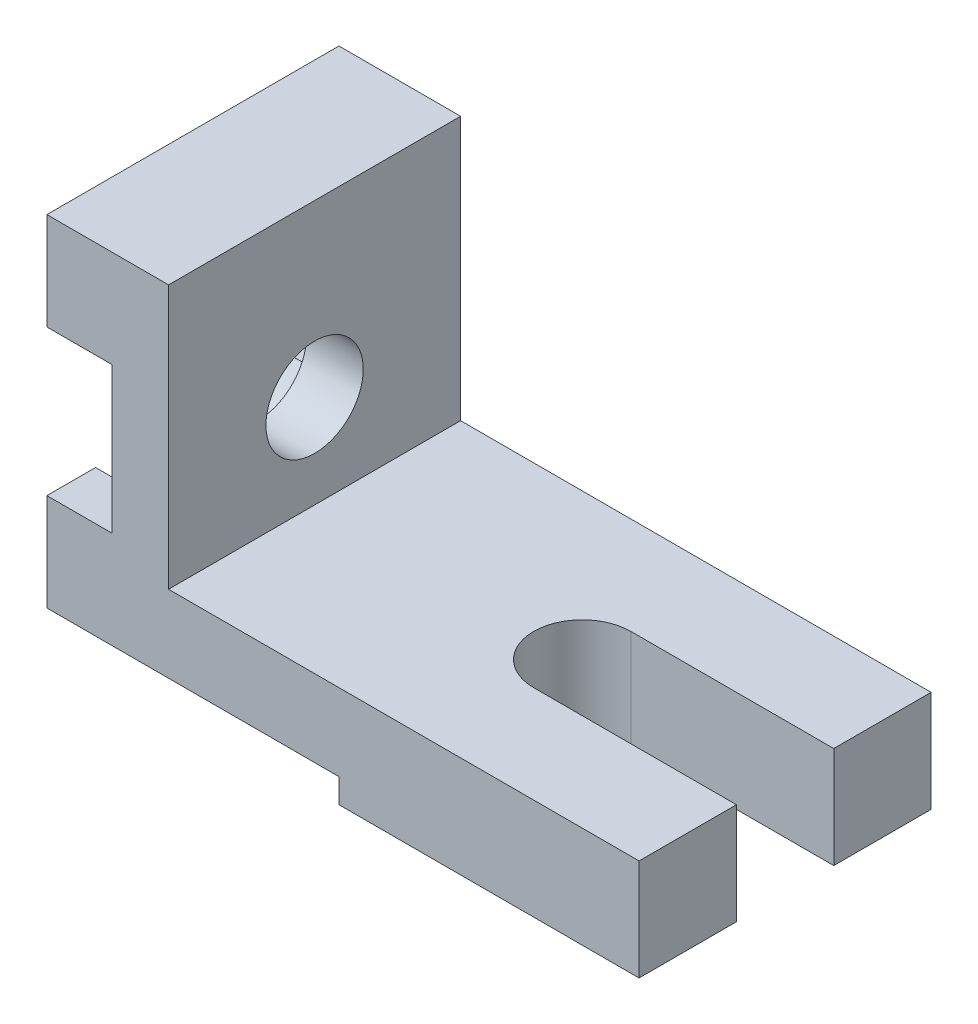
SolidWorks part; units mm, degrees
ref_plane "Front Plane" through (0, 0, 0) normal (0, 0, 1) x (1, 0, 0)
ref_plane "Top Plane" through (0, 0, 0) normal (0, 1, 0) x (1, 0, 0)
ref_plane "Right Plane" through (0, 0, 0) normal (1, 0, 0) x (0, 0, -1)
sketch "Sketch1" plane through (0, 0, 0) normal (0, 0, 1) x (1, 0, 0)
  line L0 (0, 0) -> (-146, 0)
  line L1 (-146, 0) -> (-146, 90)
  line L2 (-146, 90) -> (-116, 90)
  line L3 (-116, 90) -> (-116, 25)
  line L4 (-116, 25) -> (0, 25)
  line L5 (0, 25) -> (0, 0)
  dimension "D1" = 146
  dimension "D2" = 90
  dimension "D3" = 30
  dimension "D4" = 25
extrude "Boss-Extrude1" add sketch "Sketch1" along normal blind 72
sketch "Sketch2" plane through (0, 25, 0) normal (0, 1, 0) x (1, 0, 0)
  line L1 (-116, -72) -> (-116, 0) construction
  line L2 (0, -36) -> (-50, -36) construction
  line L3 (0, -48) -> (-50, -48)
  line L4 (0, -24) -> (-50, -24)
  line L5 (0, 0) -> (-116, 0) construction
  arc A1 (-50, -24) -> (-50, -48) centre (-50, -36) ccw
  point P4 (-25, -36)
  dimension "D2" = 12
  dimension "D1" = 50
  dimension "D3" = 66
  dimension "D4" = 36
extrude "Cut-Extrude2" cut sketch "Sketch2" against normal blind 25 and the other way through all
sketch "Sketch3" plane through (-146, 0, 0) normal (-1, 0, 0) x (0, 0, 1)
  line L4 (72, 0) -> (0, 0) construction
  line L6 (72, 0) -> (0, 0)
  line L8 (36, 0) -> (36, 48) construction
  line L9 (72, 6) -> (72, 0)
  line L10 (0, 65.664) -> (11.7517, 65.664)
  line L11 (60.2483, 65.664) -> (72, 65.664)
  line L12 (72, 6) -> (22, 6)
  line L13 (22, 6) -> (22, 0)
  line L14 (22, 0) -> (72, 0)
  circle A2 centre (36, 48) radius 30
  circle A3 centre (36, 48) radius 12
  dimension "D1" = 60
  dimension "D2" = 24
  dimension "D3" = 6
  dimension "D4" = 50
extrude "Cut-Extrude4" cut sketch "Sketch3" against normal blind 72 contours L9 L12 L13 L14
sketch "Sketch4" plane through (-146, 0, 0) normal (-1, 0, 0) x (0, 0, 1)
  line L1 (22, 0) -> (0, 0) construction
  line L2 (22, 0) -> (72, 0) construction
  line L3 (36, 0) -> (36, 18) construction
  line L4 (0, 90) -> (0, 0) construction
  line L5 (0, 66) -> (12, 66)
  line L6 (60, 66) -> (72, 66)
  line L7 (72, 90) -> (72, 6) construction
  line L11 (0, 30) -> (12, 30)
  line L12 (60, 30) -> (72, 30)
  line L13 (36, 30) -> (36, 48) construction
  line L15 (72, 6) -> (22, 6)
  line L16 (22, 6) -> (22, 0)
  line L18 (22, 6) -> (22, 0) construction
  line L19 (72, 6) -> (22, 6) construction
  line L20 (0, 66) -> (0, 30)
  line L21 (72, 66) -> (72, 30)
  arc A0 (12, 30) -> (60, 30) centre (36, 48) ccw
  arc A2 (60, 66) -> (12, 66) centre (36, 48) ccw
  line M10 (72, 6) -> (72, 90)
  line M12 (0, 90) -> (0, 0)
  dimension "D1" = 60
  dimension "D2" = 38
  dimension "D3" = 6
  dimension "D4" = 30
  dimension "D5" = 6
extrude "Cut-Extrude6" cut sketch "Sketch4" against normal blind 16 contours L6 A2 L5 L11 A0 L12 M12 M10
sketch "Sketch5" plane through (-130, 0, 0) normal (-1, 0, 0) x (0, 0, 1)
  line L0 (36, 78) -> (36, 18) construction
  line L1 (0, 48) -> (72, 48) construction
  line L2 (0, 66) -> (0, 30) construction
  line L3 (72, 30) -> (72, 66) construction
  arc A0 (60, 66) -> (12, 66) centre (36, 48) ccw construction
  arc A1 (12, 30) -> (60, 30) centre (36, 48) ccw construction
  circle A2 centre (36, 48) radius 12
  dimension "D1" = 24
extrude "Cut-Extrude7" cut sketch "Sketch5" against normal blind 16
